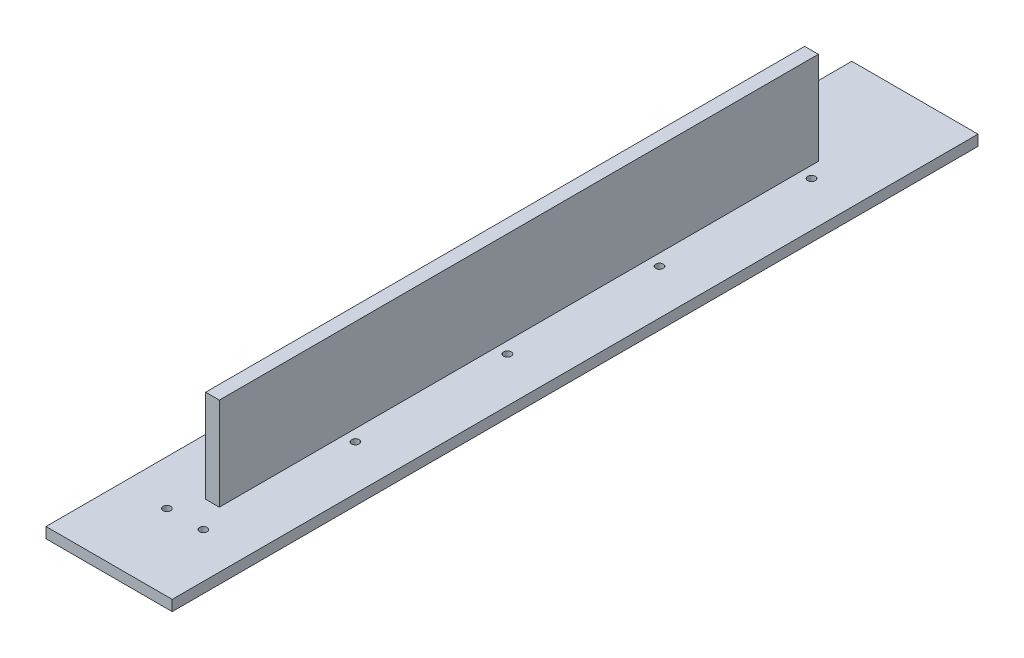
SolidWorks part; units mm, degrees
ref_plane "Plan de face" through (0, 0, 0) normal (0, 0, 1) x (1, 0, 0)
ref_plane "Plan de dessus" through (0, 0, 0) normal (0, 1, 0) x (1, 0, 0)
ref_plane "Plan de droite" through (0, 0, 0) normal (1, 0, 0) x (0, 0, -1)
sketch "Esquisse1" plane through (0, 0, 0) normal (0, 0, 1) x (1, 0, 0)
  line L0 (0, 0) -> (83, 0)
  line L1 (83, 0) -> (83, 7)
  line L2 (83, 7) -> (46, 7)
  line L3 (46, 7) -> (46, 68)
  line L4 (46, 68) -> (37, 68)
  line L5 (37, 68) -> (37, 7)
  line L6 (37, 7) -> (0, 7)
  line L7 (0, 7) -> (0, 0)
  dimension "D1" = 7
  dimension "D2" = 9
  dimension "D3" = 83
  dimension "D4" = 68
extrude "Boss.-Extru.1" add sketch "Esquisse1" along normal blind 530
sketch "Esquisse2" plane through (37, 0, 0) normal (-1, 0, 0) x (0, 0, 1)
  line L0 (530, 7) -> (0, 7) construction
  line L1 (0, 68) -> (68, 68)
  line L2 (0, 68) -> (0, 7)
  line L3 (0, 7) -> (68, 7)
  line L4 (68, 68) -> (68, 7)
  line L5 (530, 7) -> (0, 7) construction
  line L6 (530, 68) -> (462, 68)
  line L7 (530, 68) -> (530, 7)
  line L8 (530, 7) -> (462, 7)
  line L9 (462, 68) -> (462, 7)
  dimension "D1" = 68
extrude "Enlèv. mat.-Extru.1" cut sketch "Esquisse2" against normal up to vertex (9 mm away) up to point (46, 68, 0)
sketch "Esquisse3" plane through (0, 0, 0) normal (0, -1, 0) x (1, 0, 0)
  line L0 (41.5, 0) -> (41.5, 530) construction
  line L1 (0, 0) -> (83, 0) construction
  line L2 (0, 530) -> (83, 530) construction
  line L3 (29.5, 180) -> (29.5, 80) construction
  circle A0 centre (29.5, 80) radius 2.5
  circle A1 centre (53.5, 80) radius 2.5
  circle A2 centre (29.5, 180) radius 2.5
  circle A3 centre (53.5, 180) radius 2.5
  circle A4 centre (29.5, 280) radius 2.5
  circle A5 centre (53.5, 280) radius 2.5
  circle A6 centre (29.5, 380) radius 2.5
  circle A7 centre (53.5, 380) radius 2.5
  circle A8 centre (29.5, 480) radius 2.5
  circle A9 centre (53.5, 480) radius 2.5
  dimension "D1" = 5
  dimension "D2" = 12
  dimension "D3" = 80
  dimension "D5" = 100
  dimension "D4" = 5
extrude "Enlèv. mat.-Extru.2" cut sketch "Esquisse3" against normal up to vertex (7 mm away)
